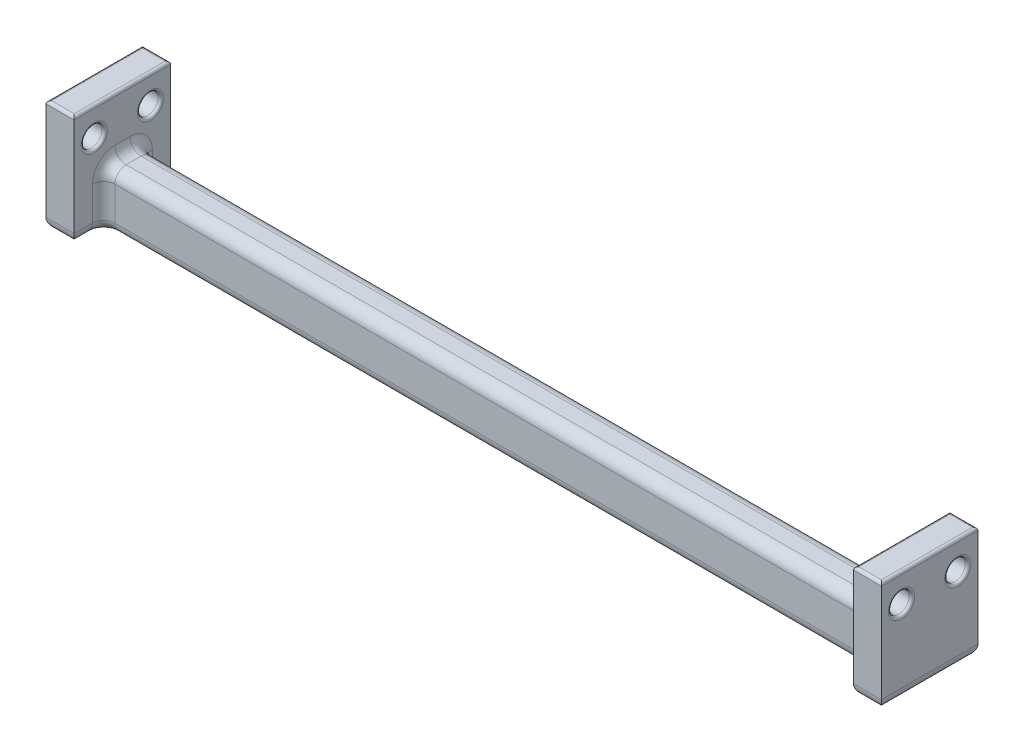
SolidWorks part; units mm, degrees
ref_plane "Front Plane" through (0, 0, 0) normal (0, 0, 1) x (1, 0, 0)
ref_plane "Top Plane" through (0, 0, 0) normal (0, 1, 0) x (1, 0, 0)
ref_plane "Right Plane" through (0, 0, 0) normal (1, 0, 0) x (0, 0, -1)
sketch "Sketch2" plane through (0, 0, 0) normal (0, 1, 0) x (1, 0, 0)
  line L0 (-88.1063, 10.922) -> (-94.4562, 10.922)
  line L1 (-94.4562, 10.922) -> (-94.4562, -10.922)
  line L2 (-94.4562, -10.922) -> (-88.1063, -10.922)
  line L3 (-88.1063, -10.922) -> (-88.1063, -4.2333)
  line L4 (-88.1063, -4.2333) -> (88.1063, -4.2333)
  line L5 (0, -4.2333) -> (0, 4.2333) construction
  line L6 (88.1063, 4.2333) -> (-88.1063, 4.2333)
  line L7 (-88.1063, 4.2333) -> (-88.1063, 10.922)
  line L8 (88.1063, 4.2333) -> (88.1063, 10.922)
  line L9 (88.1063, -10.922) -> (88.1063, -4.2333)
  line L10 (94.4562, -10.922) -> (88.1063, -10.922)
  line L11 (94.4562, 10.922) -> (94.4562, -10.922)
  line L12 (88.1063, 10.922) -> (94.4562, 10.922)
  dimension "D1" = 21.844
  dimension "D2" = 6.35
  dimension "D3" = 8.4667
  dimension "D4" = 94.4562
extrude "Boss-Extrude1" add sketch "Sketch2" along normal blind 12.7
sketch "Sketch3" plane through (0, 12.7, 0) normal (0, 1, 0) x (1, 0, 0)
  line L0 (-88.1063, 10.922) -> (-94.4562, 10.922) construction
  line L1 (-94.4562, -10.922) -> (-88.1063, -10.922)
  line L2 (-94.4562, -10.922) -> (-94.4562, 10.922)
  line L3 (-94.4562, 10.922) -> (-88.1063, 10.922)
  line L4 (-88.1063, -10.922) -> (-88.1063, 10.922)
  line L5 (-94.4562, -10.922) -> (-88.1063, 10.922) construction
  line L6 (-94.4562, 10.922) -> (-88.1063, -10.922) construction
  line L7 (-94.4562, 10.922) -> (-94.4562, -10.922) construction
  line L8 (88.1063, -10.922) -> (94.4562, -10.922)
  line L9 (88.1063, -10.922) -> (88.1063, 10.922)
  line L10 (88.1063, 10.922) -> (94.4562, 10.922)
  line L11 (94.4562, -10.922) -> (94.4562, 10.922)
  line L12 (88.1063, 10.922) -> (88.1063, 4.2333) construction
  point P0 (-91.2812, 0)
extrude "Boss-Extrude2" add sketch "Sketch3" along normal blind 12.7
sketch "Sketch4" plane through (-94.4562, 0, 0) normal (-1, 0, 0) x (0, 0, 1)
  line L0 (-10.922, 19.05) -> (10.922, 19.05) construction
  line L1 (-10.922, 25.4) -> (-10.922, 0) construction
  line L2 (10.922, 25.4) -> (10.922, 0) construction
  line L3 (-10.922, 25.4) -> (10.922, 25.4) construction
  line L4 (0, 19.05) -> (0, 25.4) construction
  circle A0 centre (-6.35, 19.05) radius 2.3368
  circle A1 centre (6.35, 19.05) radius 2.3368
  point P8 (-6.35, 19.05)
  point P9 (6.35, 19.05)
  dimension "D5" = 4.6736
  dimension "D6" = 4.6736
  dimension "D1" = 6.35
  dimension "D2" = 12.7
  dimension "D3" = 6.35
  dimension "D4" = 4.572
extrude "Cut-Extrude1" cut sketch "Sketch4" against normal through all
fillet "Fillet1" radius 2.54 20 edges at (88.1063, 12.7, 0) (-88.1063, 12.7, 0) (-91.2812, 0, -10.922) (-94.4562, 0, 0) (-91.2812, 0, 10.922) (-88.1063, 0, 7.5777) (88.1063, 0, 7.5777) (91.2812, 0, 10.922) (94.4562, 0, 0) (91.2812, 0, -10.922) (88.1063, 0, -7.5777) (-88.1063, 0, -7.5777) (-88.1063, 6.35, 4.2333) (0, 12.7, 4.2333) (88.1063, 6.35, 4.2333) (0, 0, 4.2333) (88.1063, 6.35, -4.2333) (0, 12.7, -4.2333) (-88.1063, 6.35, -4.2333) (0, 0, -4.2333)
fillet "Fillet2" radius 0.635 16 edges at (-91.2812, 25.4, 10.922) (-94.4562, 25.4, 0) (-91.2812, 25.4, -10.922) (-88.1063, 25.4, 0) (91.2812, 25.4, 10.922) (88.1063, 25.4, 0) (91.2812, 25.4, -10.922) (94.4562, 25.4, 0) (-88.1063, 19.05, -4.0132) (-94.4562, 19.05, -4.0132) (-88.1063, 19.05, 8.6868) (-94.4562, 19.05, 8.6868) (88.1063, 19.05, -8.6868) (94.4562, 19.05, -4.0132) (88.1063, 19.05, 4.0132) (94.4562, 19.05, 8.6868)
equation "\"Layer1\"= 7.5 / 2 - 1 / 32"
equation "\"D4@Sketch2\"=\"Layer1\""
